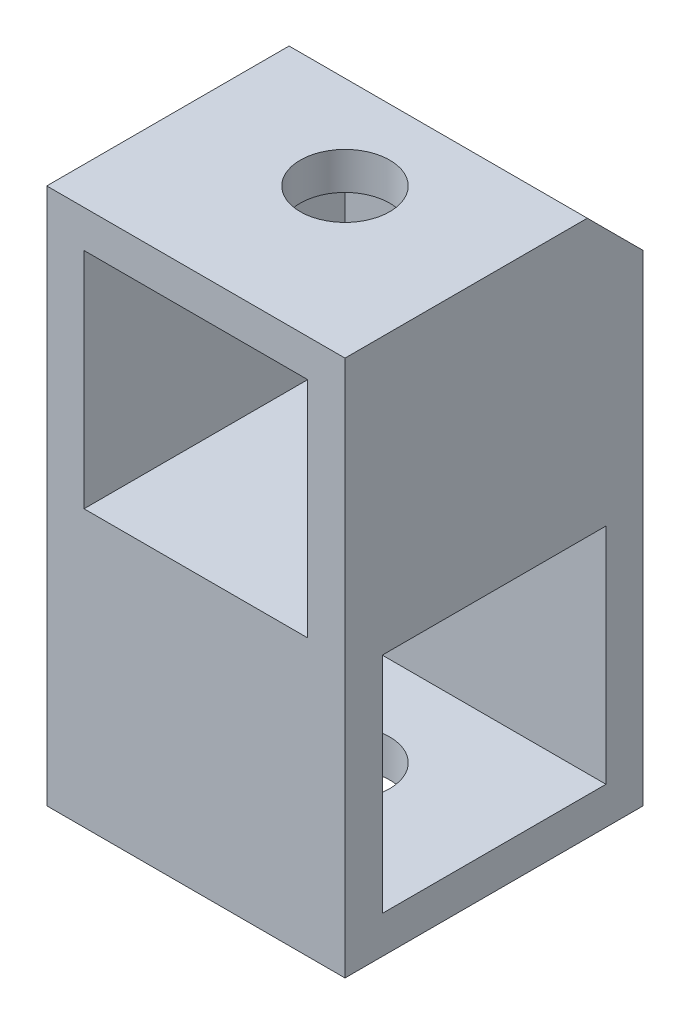
SolidWorks part; units mm, degrees
ref_plane "Front Plane" through (0, 0, 0) normal (0, 0, 1) x (1, 0, 0)
ref_plane "Top Plane" through (0, 0, 0) normal (0, 1, 0) x (1, 0, 0)
ref_plane "Right Plane" through (0, 0, 0) normal (1, 0, 0) x (0, 0, -1)
sketch "Sketch1" plane through (0, 0, 0) normal (0, 0, 1) x (1, 0, 0)
  line L0 (0, 0) -> (0, 16) construction
  line L1 (55, 0) -> (-55, 0) construction
  line L2 (-15, 31) -> (15, 31)
  line L3 (-15, 31) -> (-15, 1)
  line L4 (-15, 1) -> (15, 1)
  line L5 (15, 31) -> (15, 1)
  line L6 (-15, 31) -> (15, 1) construction
  line L7 (-15, 1) -> (15, 31) construction
  line L8 (-15, -1) -> (15, -1)
  line L9 (15, -31) -> (15, -1)
  line L10 (-15, -31) -> (15, -31)
  line L11 (-15, -31) -> (-15, -1)
  line L12 (-15, -1) -> (15, -31) construction
  line L13 (-15, -31) -> (15, -1) construction
  point P13 (0, -16)
  point P14 (0, 0)
  dimension "D2" = 30
  dimension "D1" = 16
  dimension "D3" = 30
sketch "Sketch2" plane through (0, 0, 0) normal (0, 0, 1) x (1, 0, 0)
  line L0 (-15, 31) -> (15, 31) construction
  line L1 (-20, 36) -> (20, 36)
  line L2 (-20, 36) -> (-20, -36)
  line L3 (-20, -36) -> (20, -36)
  line L4 (20, 36) -> (20, -36)
  line L5 (-20, 36) -> (20, -36) construction
  line L6 (-20, -36) -> (20, 36) construction
  line L7 (-15, 31) -> (-15, 1) construction
  point P0 (0, 0)
  dimension "D1" = 5
  dimension "D2" = 5
extrude "Boss-Extrude1" add sketch "Sketch2" along normal mid plane 40
sketch "Sketch3" plane through (0, 0, 20) normal (0, 0, 1) x (1, 0, 0)
  line L0 (-15, 1) -> (15, 31) construction
  line L1 (-15, 31) -> (15, 31)
  line L2 (-15, 31) -> (-15, 1)
  line L3 (-15, 1) -> (15, 1)
  line L4 (15, 31) -> (15, 1)
  line L5 (-15, 31) -> (15, 1) construction
  line L6 (-15, 1) -> (15, 31) construction
  point P0 (0, 16)
extrude "Cut-Extrude1" cut sketch "Sketch3" against normal offset from surface (35 mm away) 5 up to face at (0, 0, -20)
sketch "Sketch4" plane through (0, 0, 0) normal (1, 0, 0) x (0, 0, -1)
  line L1 (-15, -1) -> (15, -1)
  line L2 (-15, -1) -> (-15, -31)
  line L3 (-15, -31) -> (15, -31)
  line L4 (15, -1) -> (15, -31)
  line L5 (-15, -1) -> (15, -31) construction
  line L6 (-15, -31) -> (15, -1) construction
  point P0 (0, -16)
  point P2 (0, -16)
  dimension "D1" = 30
  dimension "D2" = 30
extrude "Cut-Extrude2" cut sketch "Sketch4" against normal through all both and the other way through all
chamfer "Chamfer1" distance 7.5 angle 45 1 edges at (0, 36, -20)
sketch "Sketch5" plane through (0, 0, 0) normal (0, 1, 0) x (1, 0, 0)
  line L0 (-15, 0) -> (15, 0) construction
  circle A0 centre (0, 0) radius 6
  dimension "D1" = 12
extrude "Cut-Extrude3" cut sketch "Sketch5" against normal through all both and the other way through all
sketch "Sketch6" plane through (0, 0, 0) normal (0, 1, 0) x (1, 0, 0)
  circle A0 centre (0, 0) radius 2.5
  circle A1 centre (0, 0) radius 6
  dimension "D1" = 5
extrude "Boss-Extrude2" add sketch "Sketch6" along normal mid plane 2
equation "\"D2@Sketch4\"=\"A\""
equation "\"D1@Sketch4\"=\"A\""
equation "\"D3@Sketch1\"=\"A\""
equation "\"D2@Sketch1\"=\"A\""
equation "\"A\"= 30mm"
equation "\"D1@Sketch1\"=(\"A\" + 2) / 2"
equation "\"D1@Boss-Extrude1\"=\"A\" + 10"
